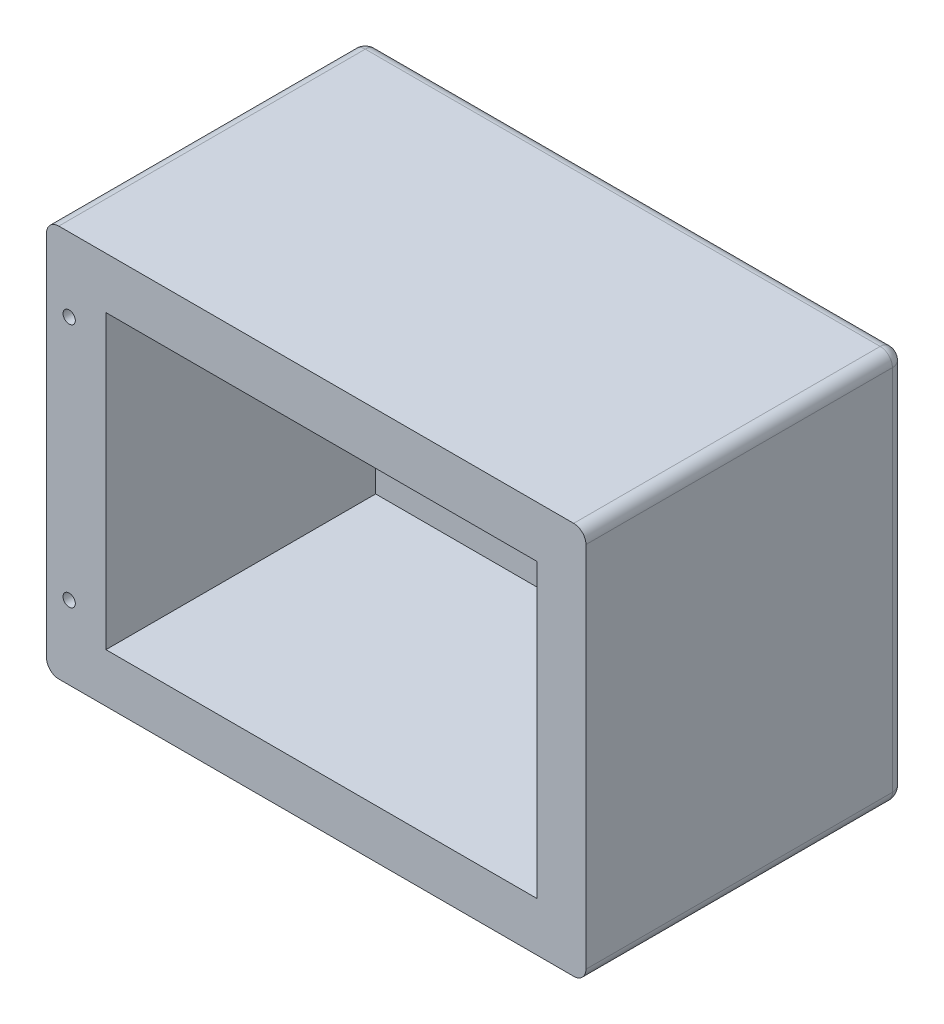
SolidWorks part; units mm, degrees
ref_plane "前视基准面" through (0, 0, 0) normal (0, 0, 1) x (1, 0, 0)
ref_plane "上视基准面" through (0, 0, 0) normal (0, 1, 0) x (1, 0, 0)
ref_plane "右视基准面" through (0, 0, 0) normal (1, 0, 0) x (0, 0, -1)
other "Configuration Table"
sketch "草图1" plane through (0, 0, 0) normal (0, 0, 1) x (1, 0, 0)
  line L0 (0, 0) -> (440, 0)
  line L1 (440, 0) -> (440, -320)
  line L2 (440, -320) -> (0, -320)
  line L3 (0, -320) -> (0, 0)
  dimension "D1" = 440
  dimension "D2" = 320
extrude "凸台-拉伸1" add sketch "草图1" along normal blind 260
sketch "草图6" plane through (0, 0, 260) normal (0, 0, 1) x (1, 0, 0)
  line L0 (440, -320) -> (440, 0) construction
  line L1 (48.4708, -41.8673) -> (400, -41.8673)
  line L2 (48.4708, -41.8673) -> (48.4708, -280)
  line L3 (48.4708, -280) -> (400, -280)
  line L4 (400, -41.8673) -> (400, -280)
  line L6 (0, -320) -> (440, -320) construction
  dimension "D1" = 40
  dimension "D2" = 40
extrude "切除-拉伸1" cut sketch "草图6" against normal blind 220
fillet "圆角1" radius 10 8 edges at (220, -320, 0) (220, 0, 0) (0, -160, 0) (0, 0, 130) (0, -320, 130) (440, -320, 130) (440, -160, 0) (440, 0, 130)
sketch "草图7" plane through (0, 0, 260) normal (0, 0, 1) x (1, 0, 0)
  line L0 (430, 0) -> (10, 0) construction
  line L1 (10, -320) -> (430, -320) construction
  line L2 (48.4708, -41.8673) -> (48.4708, -280) construction
  line L3 (48.4708, -41.8673) -> (48.4708, -280) construction
  circle A0 centre (18.4708, -60) radius 5
  circle A1 centre (18.4708, -260) radius 5
  point P13 (18.4708, -260)
  point P14 (18.4708, -60)
  dimension "D1" = 10
  dimension "D2" = 10
  dimension "D3" = 60
  dimension "D4" = 60
  dimension "D5" = 30
  dimension "D6" = 30
extrude "切除-拉伸2" cut sketch "草图7" against normal blind 10
